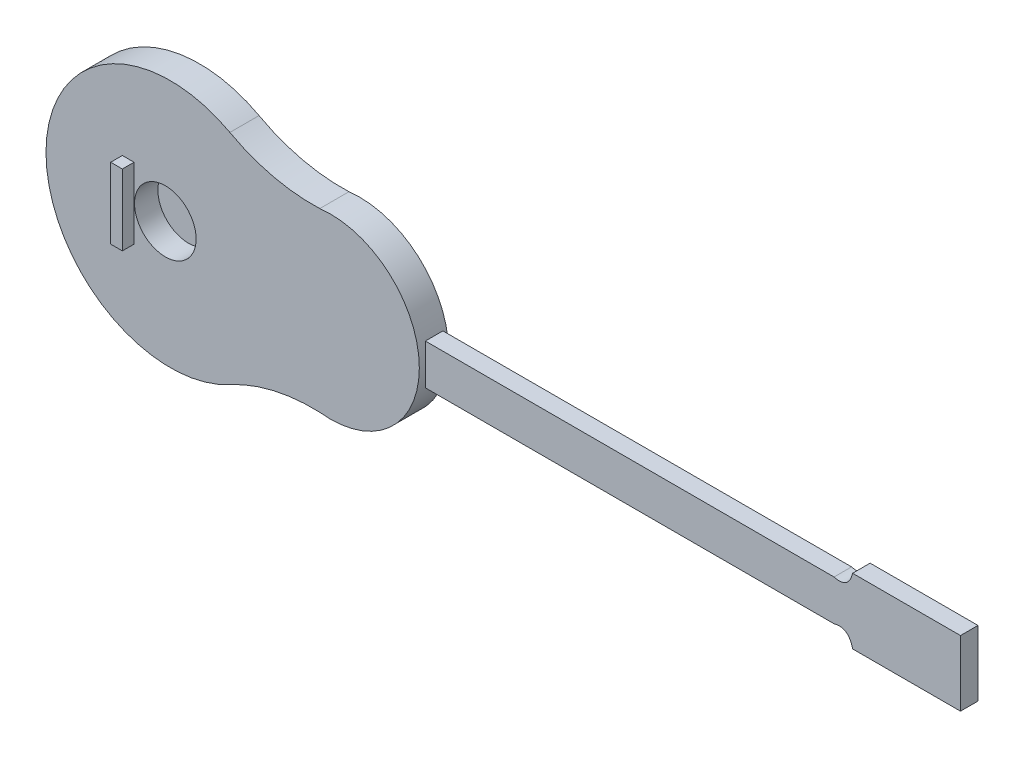
SolidWorks part; units mm, degrees
ref_plane "Front Plane" through (0, 0, 0) normal (0, 0, 1) x (1, 0, 0)
ref_plane "Top Plane" through (0, 0, 0) normal (0, 1, 0) x (1, 0, 0)
ref_plane "Right Plane" through (0, 0, 0) normal (1, 0, 0) x (0, 0, -1)
sketch "Sketch1" plane through (0, 0, 0) normal (0, 0, 1) x (1, 0, 0)
  line L0 (42.2222, 0) -> (55.214, 0) construction
  arc A0 (5.1744, 18.7041) -> (5.1744, -18.7041) centre (-5.0173, 0) ccw
  arc A1 (20.5782, -15.1127) -> (20.5782, 15.1127) centre (22.405, 0) ccw
  arc A2 (5.1744, 18.7041) -> (20.5782, 15.1127) centre (19.3685, 44.7535) ccw
  arc A3 (5.1744, -18.7041) -> (20.5782, -15.1127) centre (19.3685, -44.7535) cw
extrude "Boss-Extrude1" add sketch "Sketch1" along normal blind 5
sketch "Sketch2" plane through (0, 0, 5) normal (0, 0, 1) x (1, 0, 0)
  circle A0 centre (-5.8788, 0) radius 5.2786
extrude "Cut-Extrude1" cut sketch "Sketch2" against normal blind 4
sketch "Sketch3" plane through (0, 0, 5) normal (0, 0, 1) x (1, 0, 0)
  line L5 (-13.2372, 6.0773) -> (-11.2372, 6.0773)
  line L6 (-13.2372, 6.0773) -> (-13.2372, -6.0773)
  line L7 (-13.2372, -6.0773) -> (-11.2372, -6.0773)
  line L8 (-11.2372, 6.0773) -> (-11.2372, -6.0773)
  line L9 (-13.2372, 6.0773) -> (-11.2372, -6.0773) construction
  line L10 (-13.2372, -6.0773) -> (-11.2372, 6.0773) construction
  point P0 (-12.2372, 0)
  dimension "D1" = 2
extrude "Boss-Extrude2" add sketch "Sketch3" along normal blind 2
ref_plane "Plane1" through (37.6277, 0, 0) normal (1, 0, 0) x (0, 0, -1)
sketch "Sketch4" plane through (37.6277, 0, 0) normal (1, 0, 0) x (0, 0, -1)
  line L1 (-3.9648, 3.4705) -> (-0.9648, 3.4705)
  line L2 (-3.9648, 3.4705) -> (-3.9648, -3.4705)
  line L3 (-3.9648, -3.4705) -> (-0.9648, -3.4705)
  line L4 (-0.9648, 3.4705) -> (-0.9648, -3.4705)
  line L5 (-3.9648, 3.4705) -> (-0.9648, -3.4705) construction
  line L6 (-3.9648, -3.4705) -> (-0.9648, 3.4705) construction
  point P0 (-2.4648, 0)
  dimension "D1" = 3
extrude "Boss-Extrude3" add sketch "Sketch4" along normal blind 70 separate body
sketch "Sketch5" plane through (0, 0, 3.9648) normal (0, 0, 1) x (1, 0, 0)
  line L0 (102.5935, 0) -> (129.2852, 0) construction
  line L1 (110.8063, 5.6121) -> (129.2852, 5.6121)
  line L2 (129.2852, 5.6121) -> (129.2852, -5.6121)
  line L3 (110.8063, -5.6121) -> (129.2852, -5.6121)
  line L4 (107.6277, 3.4705) -> (107.6277, -3.4705)
  spline S0 degree 2 poles (107.6277, 3.4705) (110.1285, 2.7862) (110.8063, 5.6121) knots 0 0 0 1 1 1
  spline S1 degree 2 poles (107.6277, -3.4705) (110.1285, -2.7862) (110.8063, -5.6121) knots 0 0 0 1 1 1
extrude "Boss-Extrude4" add sketch "Sketch5" against normal blind 3
scale "Scale4" bodies to scale 103 105 scale about origin uniform scaling yes scale factor 0.5
